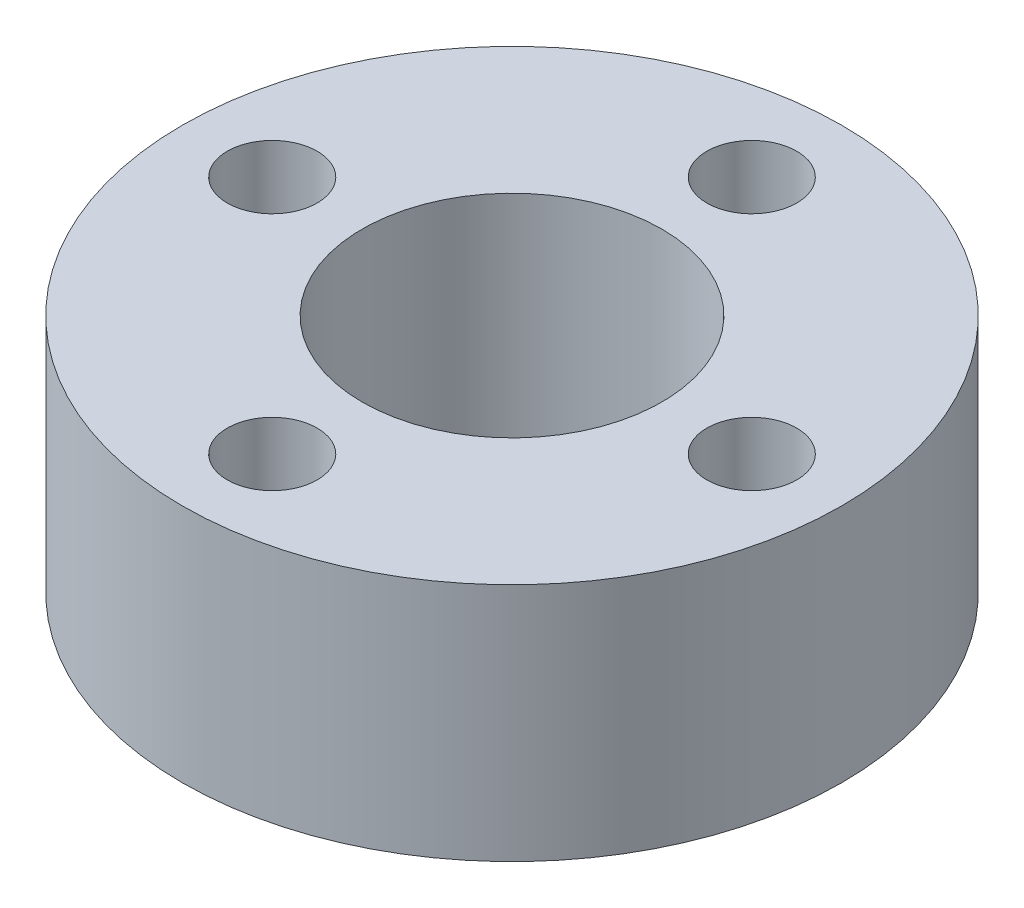
SolidWorks part; units mm, degrees
ref_plane "前视基准面" through (0, 0, 0) normal (0, 0, 1) x (1, 0, 0)
ref_plane "上视基准面" through (0, 0, 0) normal (0, 1, 0) x (1, 0, 0)
ref_plane "右视基准面" through (0, 0, 0) normal (1, 0, 0) x (0, 0, -1)
other "Configuration Table"
sketch "草图1" plane through (0, 0, 0) normal (0, 1, 0) x (1, 0, 0)
  line L0 (0, 16.2387) -> (0, -16.3226) construction
  line L1 (0, 0) -> (0, 8) construction
  circle A0 centre (0, 0) radius 11
  circle A1 centre (0, 0) radius 8 construction
  circle A2 centre (0, 0) radius 5
  circle A3 centre (0, 8) radius 1.5
  circle A4 centre (8, 0) radius 1.5
  circle A5 centre (0, -8) radius 1.5
  circle A6 centre (-8, 0) radius 1.5
  point P9 (0, 0)
  dimension "D1" = 22
  dimension "D2" = 16
  dimension "D3" = 10
  dimension "D4" = 3
  dimension "D5" = 4
  dimension "D6" = 8
extrude "凸台-拉伸1" add sketch "草图1" along normal blind 8
